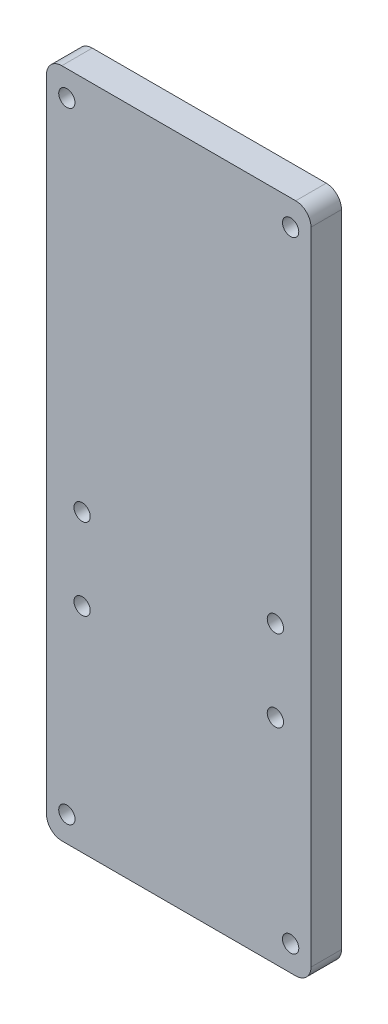
SolidWorks part; units mm, degrees
material "Balsa"
ref_plane "Front Plane" through (0, 0, 0) normal (0, 0, 1) x (1, 0, 0)
ref_plane "Top Plane" through (0, 0, 0) normal (0, 1, 0) x (1, 0, 0)
ref_plane "Right Plane" through (0, 0, 0) normal (1, 0, 0) x (0, 0, -1)
sketch "Sketch1" plane through (0, 0, 0) normal (0, 0, 1) x (1, 0, 0)
  line L0 (1.25, 61.9364) -> (93.1655, 61.9364) construction
  line L1 (23.2069, 124.9364) -> (23.2069, -1.0636)
  line L2 (26.2069, 127.9364) -> (72.2085, 127.9364)
  line L3 (71.2085, 0.9364) -> (71.2085, -12.0636) construction
  line L4 (26.2069, -4.0636) -> (72.2085, -4.0636)
  line L6 (30.2077, 53.9364) -> (68.2077, 53.9364) construction
  line L7 (30.2077, 53.9364) -> (30.2077, 37.9364) construction
  line L8 (49.2077, -12.0636) -> (49.2077, 135.9364) construction
  line L9 (30.2077, 37.9364) -> (68.2077, 37.9364) construction
  line L10 (68.2077, 53.9364) -> (68.2077, 37.9364) construction
  line L20 (75.2085, 124.9364) -> (75.2085, -1.0636)
  circle A0 centre (30.2077, 53.9364) radius 1.6
  circle A1 centre (27.2069, 0.9364) radius 1.6
  arc A2 (26.2069, -4.0636) -> (23.2069, -1.0636) centre (26.2069, -1.0636) cw
  circle A3 centre (30.2077, 37.9364) radius 1.6
  arc A4 (72.2085, -4.0636) -> (75.2085, -1.0636) centre (72.2085, -1.0636) ccw
  circle A5 centre (71.2085, 122.9364) radius 1.6
  arc A6 (72.2085, 127.9364) -> (75.2085, 124.9364) centre (72.2085, 124.9364) cw
  circle A7 centre (71.2085, 0.9364) radius 1.6
  arc A8 (26.2069, 127.9364) -> (23.2069, 124.9364) centre (26.2069, 124.9364) ccw
  circle A9 centre (68.2077, 53.9364) radius 1.6
  circle A10 centre (27.2069, 122.9364) radius 1.6
  circle A11 centre (68.2077, 37.9364) radius 1.6
  point P10 (23.2069, 61.9364)
  point P13 (49.2077, 127.9364)
  point P14 (49.2077, -4.0636)
  point P30 (75.2085, 61.9364)
  dimension "D5" = 22.0008
  dimension "D17" = 3
  dimension "D6" = 3.2
  dimension "D7" = 8
  dimension "D8" = 19
  dimension "D2" = 26.0008
  dimension "D3" = 66
  dimension "D4" = 61
  dimension "D9" = 16
extrude "Boss-Extrude1" add sketch "Sketch1" along normal blind 6
